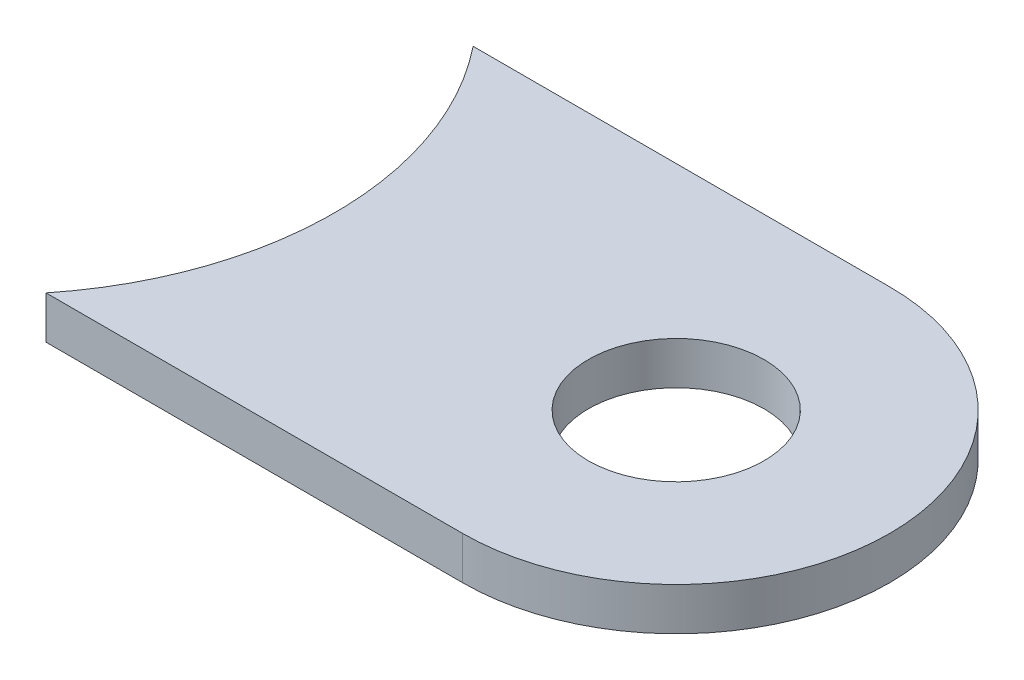
SolidWorks part; units mm, degrees
ref_plane "Front Plane" through (0, 0, 0) normal (0, 0, 1) x (1, 0, 0)
ref_plane "Top Plane" through (0, 0, 0) normal (0, 1, 0) x (1, 0, 0)
ref_plane "Right Plane" through (0, 0, 0) normal (1, 0, 0) x (0, 0, -1)
sketch "Sketch1" plane through (0, 0, 0) normal (0, 1, 0) x (1, 0, 0)
  line L0 (-25.4, 7.9375) -> (0, 7.9375)
  line L1 (0, -7.9375) -> (-25.4, -7.9375)
  line L2 (-25.4, -7.9375) -> (-25.4, 7.9375)
  circle A0 centre (0, 0) radius 3.2639
  arc A1 (0, 7.9375) -> (0, -7.9375) centre (0, 0) cw
  dimension "D1" = 6.5278
  dimension "D2" = 15.875
  dimension "D3" = 25.4
extrude "Boss-Extrude1" add sketch "Sketch1" along normal blind 1.5875
sketch "Sketch2" plane through (0, 1.5875, 0) normal (0, 1, 0) x (1, 0, 0)
  line L0 (-25.4, 7.9375) -> (-25.4, -7.9375) construction
  circle A0 centre (-25.4, 0) radius 12.7
  dimension "D1" = 25.4
extrude "Cut-Extrude1" cut sketch "Sketch2" against normal through all
